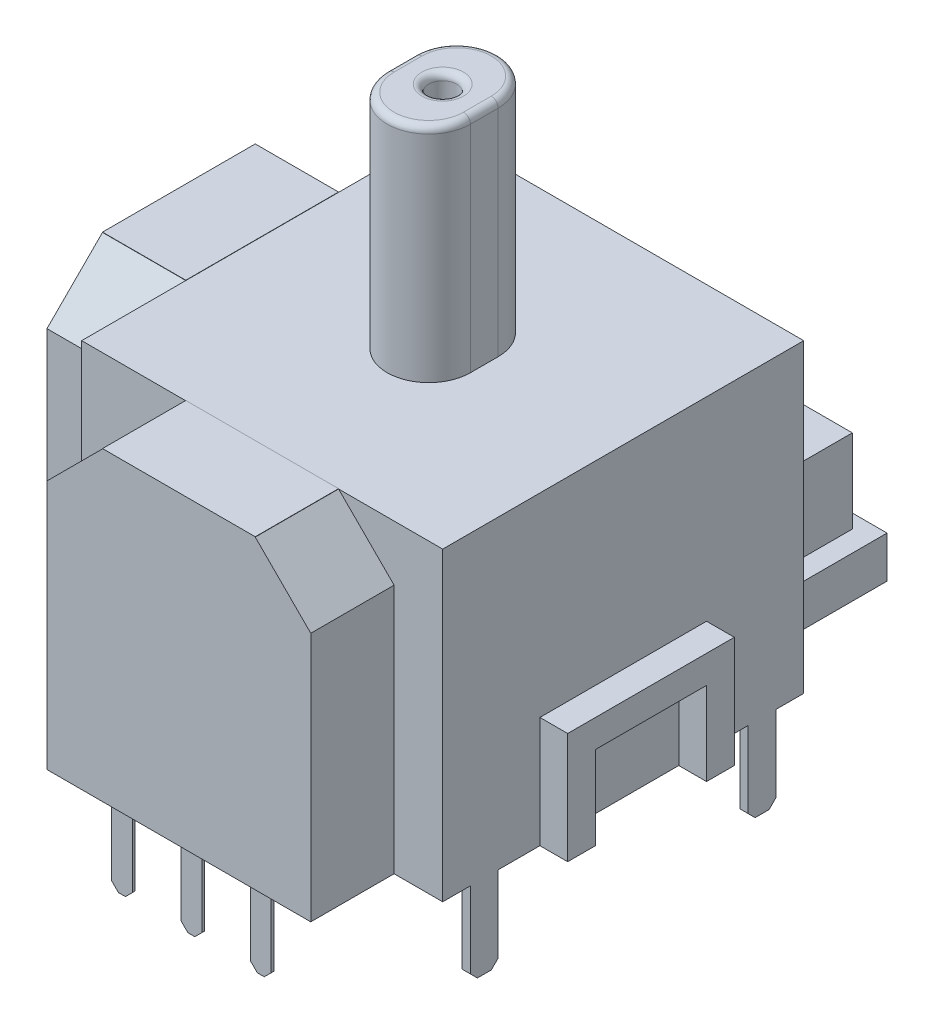
SolidWorks part; units mm, degrees
material "ABS"
ref_plane "Front" through (0, 0, 0) normal (0, 0, 1) x (1, 0, 0)
ref_plane "Top" through (0, 0, 0) normal (0, 1, 0) x (1, 0, 0)
ref_plane "Right" through (0, 0, 0) normal (1, 0, 0) x (0, 0, -1)
sketch "Sketch2" plane through (0, 0, 0) normal (1, 0, 0) x (0, 0, -1)
  line L1 (-6.5, 5.5) -> (6.5, 5.5)
  line L2 (-6.5, 5.5) -> (-6.5, -5.5)
  line L3 (-6.5, -5.5) -> (6.5, -5.5)
  line L4 (6.5, 5.5) -> (6.5, -5.5)
  line L5 (-6.5, 5.5) -> (6.5, -5.5) construction
  line L6 (-6.5, -5.5) -> (6.5, 5.5) construction
  point P0 (0, 0)
  dimension "D1" = 13
  dimension "D2" = 11
extrude "Boss-Extrude1" add sketch "Sketch2" along normal mid plane 13
sketch "Sketch3" plane through (6.5, 0, 0) normal (1, 0, 0) x (0, 0, -1)
  line L0 (-3, -1.5) -> (-3, -5.5)
  line L1 (-3, -1.5) -> (3, -1.5)
  line L2 (-3, -5.5) -> (3, -5.5)
  line L3 (3, -1.5) -> (3, -5.5)
  line L4 (-3, -1.5) -> (3, -5.5) construction
  line L5 (-3, -5.5) -> (3, -1.5) construction
  line L6 (-6.5, -5.5) -> (6.5, -5.5) construction
  line L7 (-6.5, -5.5) -> (6.5, -5.5) construction
  line L8 (-2, -2.5) -> (2, -2.5)
  line L9 (-2, -2.5) -> (-2, -5.5)
  line L10 (-2, -5.5) -> (2, -5.5)
  line L11 (2, -2.5) -> (2, -5.5)
  point P0 (0, -5.5)
  point P1 (0, -3.5)
  point P2 (0, -5.5)
  line M7 (-6.5, -5.5) -> (6.5, -5.5)
  dimension "D1" = 6
  dimension "D2" = 4
  dimension "D3" = 1
  dimension "D4" = 1
extrude "Boss-Extrude2" add sketch "Sketch3" along normal blind 1 contours L8 L11 L3 L1 L0 L9 M7
sketch "Sketch4" plane through (0, 0, 6.5) normal (0, 0, 1) x (1, 0, 0)
  line L0 (6.5, -5.5) -> (-6.5, -5.5) construction
  line L1 (-4.75, -5.5) -> (4.75, -5.5)
  line L2 (-4.75, -5.5) -> (-4.75, 5.5)
  line L3 (-4.75, 5.5) -> (4.75, 5.5)
  line L4 (4.75, -5.5) -> (4.75, 5.5)
  line L5 (6.5, 5.5) -> (-6.5, 5.5) construction
  point P4 (0, -5.5)
  dimension "D1" = 9.5
extrude "Boss-Extrude3" add sketch "Sketch4" along normal blind 3
chamfer "Chamfer1" distance 2 angle 45 2 edges at (4.75, 5.5, 8) (-4.75, 5.5, 8)
sketch "Sketch5" plane through (-6.5, 0, 0) normal (-1, 0, 0) x (0, 0, 1)
  line L0 (6.5, -5.5) -> (-6.5, -5.5) construction
  line L1 (-4.75, 5.5) -> (4.75, 5.5)
  line L2 (-4.75, 5.5) -> (-4.75, -5.5)
  line L3 (-4.75, -5.5) -> (4.75, -5.5)
  line L4 (4.75, 5.5) -> (4.75, -5.5)
  line L5 (-6.5, 5.5) -> (6.5, 5.5) construction
  point P5 (0, -5.5)
  dimension "D1" = 9.5
extrude "Boss-Extrude4" add sketch "Sketch5" along normal blind 3
chamfer "Chamfer2" distance 2 angle 45 2 edges at (-8, 5.5, -4.75) (-8, 5.5, 4.75)
sketch "Sketch6" plane through (0, 0, -6.5) normal (0, 0, -1) x (-1, 0, 0)
  line L0 (-6.5, -5.5) -> (6.5, -5.5) construction
  line L1 (-4.5, -5.5) -> (4.5, -5.5)
  line L2 (-4.5, -5.5) -> (-4.5, -4)
  line L3 (-4.5, -4) -> (4.5, -4)
  line L4 (4.5, -5.5) -> (4.5, -4)
  point P4 (0, -5.5)
  dimension "D1" = 9
  dimension "D2" = 1.5
extrude "Boss-Extrude5" add sketch "Sketch6" along normal blind 5
sketch "Sketch7" plane through (0, 0, -6.5) normal (0, 0, -1) x (-1, 0, 0)
  line L0 (4.5, -4) -> (-4.5, -4) construction
  line L1 (-3.75, -4) -> (3.75, -4)
  line L2 (-3.75, -4) -> (-3.75, -1)
  line L3 (-3.75, -1) -> (3.75, -1)
  line L4 (3.75, -4) -> (3.75, -1)
  point P4 (0, -4)
  dimension "D1" = 3
  dimension "D2" = 7.5
extrude "Boss-Extrude6" add sketch "Sketch7" along normal blind 4.5
sketch "Sketch8" plane through (0, 5.5, 0) normal (0, 1, 0) x (1, 0, 0)
  line L0 (0, 0.5) -> (0, -0.5) construction
  line L1 (1.5, 0.5) -> (1.5, -0.5)
  line L2 (-1.5, 0.5) -> (-1.5, -0.5)
  arc A0 (1.5, 0.5) -> (-1.5, 0.5) centre (0, 0.5) ccw
  arc A1 (-1.5, -0.5) -> (1.5, -0.5) centre (0, -0.5) ccw
  circle A2 centre (0, 0) radius 0.5
  point P3 (0, 0)
  dimension "D2" = 4
  dimension "D1" = 3
extrude "Boss-Extrude7" add sketch "Sketch8" along normal blind 8
fillet "Fillet2" radius 0.25 5 edges at (0, 13.5, 0.5) (1.5, 13.5, 0) (0, 13.5, 2) (-1.5, 13.5, 0) (0, 13.5, -2)
sketch "Sketch9" plane through (0, 5.5, 0) normal (0, 1, 0) x (1, 0, 0)
  line L0 (-9.5, -2.75) -> (-6.5, -2.75) construction
  line L1 (-9.5, 2.75) -> (-6.5, 2.75)
  line L2 (-9.5, 2.75) -> (-9.5, -2.75)
  line L3 (-9.5, -2.75) -> (-6.5, -2.75)
  line L4 (-6.5, 2.75) -> (-6.5, -2.75)
  line L5 (-6.5, -2.75) -> (-6.5, -4.75) construction
  line L7 (-2.75, -6.5) -> (2.75, -6.5)
  line L8 (-2.75, -6.5) -> (-2.75, -9.5)
  line L9 (-2.75, -9.5) -> (2.75, -9.5)
  line L10 (2.75, -6.5) -> (2.75, -9.5)
extrude "Boss-Extrude8" add sketch "Sketch9" along normal blind 0.01
sketch "Sketch10" plane through (0, -5.5, 0) normal (0, -1, 0) x (1, 0, 0)
  line L0 (-6.5, -6.5) -> (-6.5, -2.75) construction
  line L1 (-6.5, -5.5) -> (-6.2, -5.5)
  line L2 (-6.5, -5.5) -> (-6.5, -4.5)
  line L3 (-6.5, -4.5) -> (-6.2, -4.5)
  line L4 (-6.2, -5.5) -> (-6.2, -4.5)
  line L5 (6.5, -6.5) -> (6.5, 6.5) construction
  line L6 (6.5, -5.5) -> (6.2, -5.5)
  line L7 (6.5, -5.5) -> (6.5, -4.5)
  line L8 (6.5, -4.5) -> (6.2, -4.5)
  line L9 (6.2, -5.5) -> (6.2, -4.5)
  line L10 (-6.5, 2.75) -> (-6.5, 6.5) construction
  line L11 (-6.5, 5.5) -> (-6.2, 5.5)
  line L12 (-6.5, 5.5) -> (-6.5, 4.5)
  line L13 (-6.5, 4.5) -> (-6.2, 4.5)
  line L14 (-6.2, 5.5) -> (-6.2, 4.5)
  line L15 (-6.5, 5) -> (-6.2, 5) construction
  line L16 (6.5, 5.5) -> (6.2, 5.5)
  line L17 (6.5, 5.5) -> (6.5, 4.5)
  line L18 (6.5, 4.5) -> (6.2, 4.5)
  line L19 (6.2, 5.5) -> (6.2, 4.5)
  line L20 (-9.2, -0.375) -> (-9.1, -0.375)
  line L21 (-6.35, -4.5) -> (-6.35, 4.5) construction
  line L22 (0, 0) -> (-6.35, 0) construction
  line L23 (-9.2, -0.375) -> (-9.2, 0.375)
  line L24 (-9.2, 0.375) -> (-9.1, 0.375)
  line L25 (-9.1, -0.375) -> (-9.1, 0.375)
  line L26 (-9.2, -0.375) -> (-9.1, 0.375) construction
  line L27 (-9.2, 0.375) -> (-9.1, -0.375) construction
  line L28 (-9.2, -2.875) -> (-9.1, -2.875)
  line L29 (-9.2, -2.875) -> (-9.2, -2.125)
  line L30 (-9.2, -2.125) -> (-9.1, -2.125)
  line L31 (-9.1, -2.875) -> (-9.1, -2.125)
  line L32 (-9.2, -2.875) -> (-9.1, -2.125) construction
  line L33 (-9.2, -2.125) -> (-9.1, -2.875) construction
  line L34 (-9.2, 2.125) -> (-9.1, 2.125)
  line L35 (-9.2, 2.125) -> (-9.2, 2.875)
  line L36 (-9.2, 2.875) -> (-9.1, 2.875)
  line L37 (-9.1, 2.125) -> (-9.1, 2.875)
  line L38 (-9.2, 2.125) -> (-9.1, 2.875) construction
  line L39 (-9.2, 2.875) -> (-9.1, 2.125) construction
  line L40 (0, 0) -> (0, 9) construction
  line L41 (-0.375, 8.95) -> (0.375, 8.95)
  line L42 (-0.375, 8.95) -> (-0.375, 9.05)
  line L43 (-0.375, 9.05) -> (0.375, 9.05)
  line L44 (0.375, 8.95) -> (0.375, 9.05)
  line L45 (-0.375, 8.95) -> (0.375, 9.05) construction
  line L46 (-0.375, 9.05) -> (0.375, 8.95) construction
  line L47 (-6.5, -5) -> (-6.2, -5) construction
  line L48 (-2.875, 8.95) -> (-2.125, 8.95)
  line L49 (-2.875, 8.95) -> (-2.875, 9.05)
  line L50 (-2.875, 9.05) -> (-2.125, 9.05)
  line L51 (-2.125, 8.95) -> (-2.125, 9.05)
  line L52 (-2.875, 8.95) -> (-2.125, 9.05) construction
  line L53 (-2.875, 9.05) -> (-2.125, 8.95) construction
  line L54 (2.125, 8.95) -> (2.875, 8.95)
  line L55 (2.125, 8.95) -> (2.125, 9.05)
  line L56 (2.125, 9.05) -> (2.875, 9.05)
  line L57 (2.875, 8.95) -> (2.875, 9.05)
  line L58 (2.125, 8.95) -> (2.875, 9.05) construction
  line L59 (2.125, 9.05) -> (2.875, 8.95) construction
  line L60 (-3.225, -5.625) -> (-2.975, -5.625)
  line L61 (-3.225, -5.625) -> (-3.225, -5.375)
  line L62 (-3.225, -5.375) -> (-2.975, -5.375)
  line L63 (-2.975, -5.625) -> (-2.975, -5.375)
  line L64 (-3.225, -5.625) -> (-2.975, -5.375) construction
  line L65 (-3.225, -5.375) -> (-2.975, -5.625) construction
  line L66 (2.775, -5.625) -> (3.025, -5.625)
  line L67 (2.775, -5.625) -> (2.775, -5.375)
  line L68 (2.775, -5.375) -> (3.025, -5.375)
  line L69 (3.025, -5.625) -> (3.025, -5.375)
  line L70 (2.775, -5.625) -> (3.025, -5.375) construction
  line L71 (2.775, -5.375) -> (3.025, -5.625) construction
  line L72 (2.775, -9.625) -> (3.025, -9.625)
  line L73 (2.775, -9.625) -> (2.775, -9.375)
  line L74 (2.775, -9.375) -> (3.025, -9.375)
  line L75 (3.025, -9.625) -> (3.025, -9.375)
  line L76 (2.775, -9.625) -> (3.025, -9.375) construction
  line L77 (2.775, -9.375) -> (3.025, -9.625) construction
  line L78 (-3.225, -9.625) -> (-2.975, -9.625)
  line L79 (-3.225, -9.625) -> (-3.225, -9.375)
  line L80 (-3.225, -9.375) -> (-2.975, -9.375)
  line L81 (-2.975, -9.625) -> (-2.975, -9.375)
  line L82 (-3.225, -9.625) -> (-2.975, -9.375) construction
  line L83 (-3.225, -9.375) -> (-2.975, -9.625) construction
  point P22 (-9.15, 0)
  point P31 (-9.15, -2.5)
  point P37 (-9.15, 2.5)
  point P42 (0, 9)
  point P47 (2.5, 9)
  point P51 (-2.5, 9)
  point P60 (2.9, -5.5)
  point P65 (2.9, -9.5)
  point P66 (-3.1, -5.5)
  point P75 (-3.1, -9.5)
  point P87 (-6.35, -5)
  dimension "D1" = 0.3
  dimension "D2" = 1
  dimension "D3" = 11
  dimension "D4" = 2.5
  dimension "D5" = 2.5
  dimension "D6" = 0.1
  dimension "D7" = 0.75
  dimension "D8" = 3
  dimension "D9" = 4
  dimension "D10" = 2.5
  dimension "D11" = 0.75
  dimension "D12" = 0.1
  dimension "D13" = 2.5
  dimension "D14" = 0.5
  dimension "D15" = 4
  dimension "D16" = 6
  dimension "D17" = 3.25
  dimension "D18" = 0.25
extrude "Boss-Extrude9" add sketch "Sketch10" along normal blind 3
chamfer "Chamfer3" distance 0.25 angle 45 20 edges at (-9.15, -8.5, 2.875) (-9.15, -8.5, 2.125) (-9.15, -8.5, 0.375) (-9.15, -8.5, -0.375) (-9.15, -8.5, -2.875) (-9.15, -8.5, -2.125) (-6.35, -8.5, 5.5) (-6.35, -8.5, 4.5) (6.35, -8.5, 5.5) (6.35, -8.5, 4.5) (6.35, -8.5, -5.5) (6.35, -8.5, -4.5) (-6.35, -8.5, -4.5) (-6.35, -8.5, -5.5) (2.875, -8.5, 9) (2.125, -8.5, 9) (0.375, -8.5, 9) (-0.375, -8.5, 9) (-2.125, -8.5, 9) (-2.875, -8.5, 9)
chamfer "Chamfer4" distance 0.1 angle 45 16 edges at (2.9, -8.5, -5.625) (2.775, -8.5, -5.5) (2.9, -8.5, -5.375) (3.025, -8.5, -5.5) (-3.1, -8.5, -5.625) (-3.225, -8.5, -5.5) (-3.1, -8.5, -5.375) (-2.975, -8.5, -5.5) (-3.1, -8.5, -9.625) (-3.225, -8.5, -9.5) (-3.1, -8.5, -9.375) (-2.975, -8.5, -9.5) (2.9, -8.5, -9.625) (2.775, -8.5, -9.5) (2.9, -8.5, -9.375) (3.025, -8.5, -9.5)
